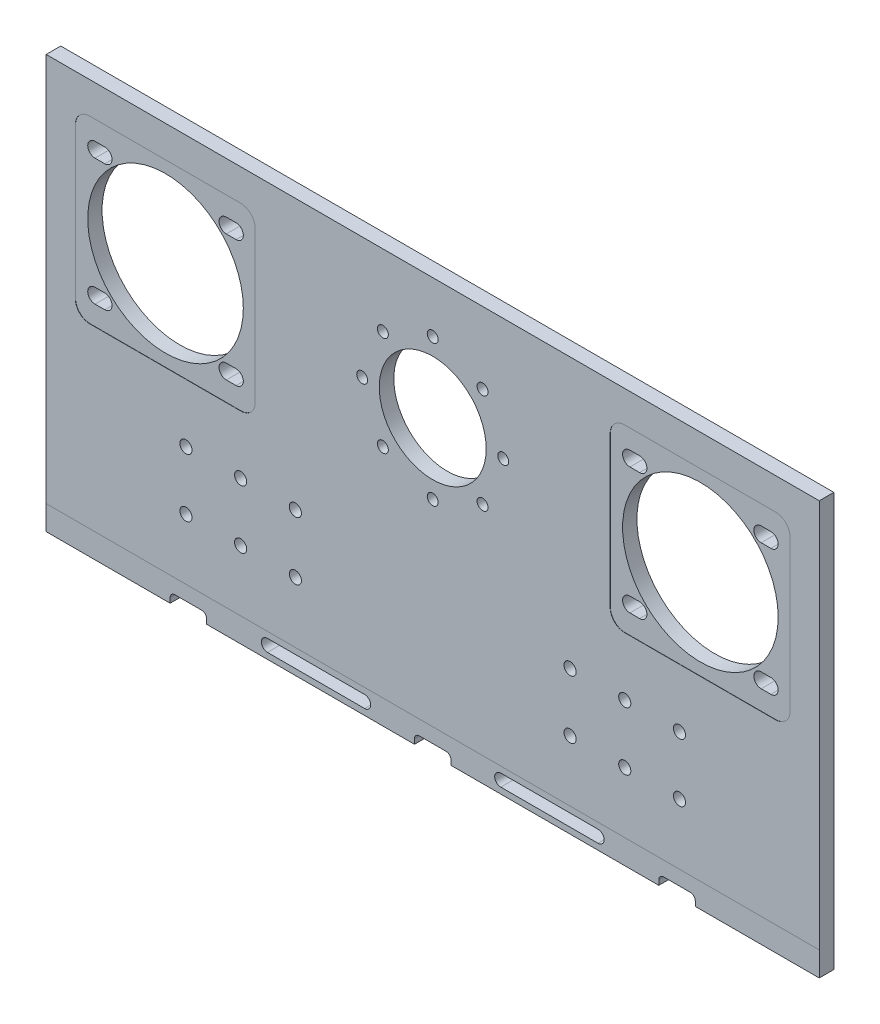
SolidWorks part; units mm, degrees
material "Сталь 45 ГОСТ 1050-88"
ref_plane "Front Plane" through (0, 0, 0) normal (0, 0, 1) x (1, 0, 0)
ref_plane "Top Plane" through (0, 0, 0) normal (0, 1, 0) x (1, 0, 0)
ref_plane "Right Plane" through (0, 0, 0) normal (1, 0, 0) x (0, 0, -1)
sketch "Skizze1" plane through (0, 0, 0) normal (0, 0, 1) x (1, 0, 0)
  line L0 (35, -0.0567) -> (-75, -0.0567)
  line L1 (-75, -0.0567) -> (-185, -0.0567)
  line L2 (35, -50.0567) -> (35, -50.5567)
  line L3 (35, -0.0567) -> (70, -0.0567)
  line L6 (-75, -0.0567) -> (-75, 49.9433)
  line L7 (-75, -0.0567) -> (-75, -110.0567)
  line L8 (0, 25.7745) -> (0, -25.8879)
  line L9 (9.1688, -35.0567) -> (60.8312, -35.0567)
  line L10 (70, -25.8879) -> (70, 25.7745)
  line L11 (60.8312, 34.9433) -> (9.1688, 34.9433)
  line L12 (35, -0.0567) -> (35, -35.0567)
  line L13 (35, -35.0567) -> (70, -35.0567)
  line L14 (70, -0.0567) -> (70, -35.0567)
  line L15 (35, -0.0567) -> (14, -0.0567)
  line L16 (35, -0.0567) -> (35, -50.0567)
  line L19 (35, -0.0567) -> (14, -0.0567)
  line L20 (35, -0.0567) -> (35, 49.9433)
  line L23 (-185, -0.0567) -> (-234, -0.0567)
  line L24 (-185, -0.0567) -> (-185, 49.9433)
  line L25 (-185, 49.9433) -> (-234, 49.9433)
  line L27 (-234, -0.0567) -> (-185, -0.0567)
  line L30 (-185, -0.0567) -> (-185, -50.0567)
  line L31 (-234, 49.9433) -> (84, 49.9433)
  line L33 (-234, -0.0567) -> (14, -0.0567)
  line L35 (14, -0.0567) -> (-234, -0.0567)
  line L39 (-143, -117.5567) -> (-103, -117.5567)
  line L41 (-143, -112.5567) -> (-103, -112.5567)
  line L43 (-7, -117.5567) -> (-47, -117.5567)
  line L44 (-7, -112.5567) -> (-47, -112.5567)
  line L51 (-75, -110.0567) -> (-75, -116.0567)
  line L53 (-67.5, -120.0567) -> (18, -120.0567)
  line L58 (33, -120.0567) -> (84, -120.0567)
  line L59 (-168, -120.0567) -> (-82.5, -120.0567)
  line L66 (33, -118.0567) -> (33, -120.0567)
  line L67 (20, -116.0567) -> (31, -116.0567)
  line L68 (18, -120.0567) -> (18, -118.0567)
  line L70 (-67.5, -118.0567) -> (-67.5, -120.0567)
  line L71 (-80.5, -116.0567) -> (-69.5, -116.0567)
  line L72 (-82.5, -120.0567) -> (-82.5, -118.0567)
  line L74 (-168, -118.0567) -> (-168, -120.0567)
  line L75 (-181, -116.0567) -> (-170, -116.0567)
  line L76 (-183, -120.0567) -> (-183, -118.0567)
  line L77 (-234, -120.0567) -> (-183, -120.0567)
  line L78 (-234, 49.9433) -> (-234, -120.0567)
  line L79 (84, -110.0567) -> (-234, -110.0567)
  line L80 (84, -120.0567) -> (84, 49.9433)
  circle A0 centre (-185, -0.0567) radius 15
  circle A1 centre (35, -0.0567) radius 15
  circle A2 centre (-75, -0.0567) radius 60
  circle A3 centre (-75, -0.0567) radius 22
  arc A4 (-183, -118.0567) -> (-181, -116.0567) centre (-181, -118.0567) cw
  arc A6 (-170, -116.0567) -> (-168, -118.0567) centre (-170, -118.0567) cw
  arc A8 (9.1688, 34.9433) -> (0, 25.7745) centre (35, -0.0567) ccw
  arc A9 (0, -25.8879) -> (9.1688, -35.0567) centre (35, -0.0567) ccw
  arc A10 (60.8312, -35.0567) -> (70, -25.8879) centre (35, -0.0567) ccw
  arc A11 (70, 25.7745) -> (60.8312, 34.9433) centre (35, -0.0567) ccw
  arc A12 (-82.5, -118.0567) -> (-80.5, -116.0567) centre (-80.5, -118.0567) cw
  circle A14 centre (35, -0.1133) radius 27.5
  circle A15 centre (35, -0.0567) radius 32
  circle A16 centre (-185, -0.0567) radius 32
  arc A17 (-67.5, -118.0567) -> (-69.5, -116.0567) centre (-69.5, -118.0567) ccw
  arc A18 (18, -118.0567) -> (20, -116.0567) centre (20, -118.0567) cw
  arc A19 (33, -118.0567) -> (31, -116.0567) centre (31, -118.0567) ccw
  arc A23 (-143, -112.5567) -> (-143, -117.5567) centre (-143, -115.0567) ccw
  arc A24 (-103, -117.5567) -> (-103, -112.5567) centre (-103, -115.0567) ccw
  arc A25 (-7, -117.5567) -> (-7, -112.5567) centre (-7, -115.0567) ccw
  arc A26 (-47, -112.5567) -> (-47, -117.5567) centre (-47, -115.0567) ccw
  point P49 (-169, -118.5631)
  point P63 (-103, -110.0567)
  point P67 (0, -50.5567)
  point P69 (0, -50.0567)
  point P80 (-83, -118.7422)
extrude "Aufsatz-Linear austragen1" add sketch "Skizze1" along normal blind 6
sketch "Skizze2" plane through (0, 0, 0) normal (0, 0, 1) x (1, 0, 0)
  circle A1 centre (-75, -0.0567) radius 12.5
  circle A2 centre (-75, -0.0567) radius 29
  point P1 (-75, 28.9433)
  point P4 (-75, 19.9433)
  point P7 (-54.4939, 20.4494)
  point P8 (-60.8579, 14.0855)
  point P9 (-55, -0.0567)
  point P10 (-60.8579, -14.1988)
  point P11 (-75, -20.0567)
  point P12 (-89.1421, -14.1988)
  point P13 (-95, -0.0567)
  point P14 (-89.1421, 14.0855)
  point P15 (-75, -0.0567)
  point P16 (-46, -0.0567)
  point P17 (-54.4939, -20.5628)
  point P18 (-75, -29.0567)
  point P19 (-95.5061, -20.5628)
  point P20 (-104, -0.0567)
  point P21 (-95.5061, 20.4494)
  point P22 (-75, -0.0567)
sketch "Skizze4" plane through (0, 0, 6) normal (0, 0, 1) x (1, 0, 0)
  line L0 (-214, -23.0567) -> (-210, -23.0567)
  line L2 (-210, 28.9433) -> (-214, 28.9433)
  line L8 (-75, -0.0567) -> (-75, -35.2993) construction
  line L9 (64, 22.9433) -> (60, 22.9433)
  line L11 (-210, -29.0567) -> (-214, -29.0567)
  line L12 (-156, -23.0567) -> (-160, -23.0567)
  line L15 (-160, -29.0567) -> (-156, -29.0567)
  line L16 (-156, 22.9433) -> (-160, 22.9433)
  line L19 (-160, 28.9433) -> (-156, 28.9433)
  line L20 (66, -37.0567) -> (4, -37.0567)
  line L26 (-234, 49.9433) -> (-234, -120.0567)
  line L27 (-234, 49.9433) -> (-234, -100.0567)
  line L28 (-185, 36.9433) -> (-216, 36.9433)
  line L29 (-185, 36.9433) -> (-154, 36.9433)
  line L30 (-148, 30.9433) -> (-148, -31.0567)
  line L31 (-222, 30.9433) -> (-222, -31.0567)
  line L32 (-216, -37.0567) -> (-154, -37.0567)
  line L33 (72, 30.9433) -> (72, -31.0567)
  line L34 (-2, 30.9433) -> (-2, -31.0567)
  line L35 (35, 36.9433) -> (4, 36.9433)
  line L37 (-214, 22.9433) -> (-210, 22.9433)
  line L39 (35, 36.9433) -> (66, 36.9433)
  line L40 (84, 49.9433) -> (84, -100.0567)
  line L41 (10, 28.9433) -> (6, 28.9433)
  line L42 (6, 22.9433) -> (10, 22.9433)
  line L43 (10, -29.0567) -> (6, -29.0567)
  line L44 (6, -23.0567) -> (10, -23.0567)
  line L45 (60, -29.0567) -> (64, -29.0567)
  line L46 (60, 28.9433) -> (64, 28.9433)
  line L47 (64, -23.0567) -> (60, -23.0567)
  circle A19 centre (-185, -0.0567) radius 30
  arc A20 (-148, -31.0567) -> (-154, -37.0567) centre (-154, -31.0567) cw
  arc A21 (-222, -31.0567) -> (-216, -37.0567) centre (-216, -31.0567) ccw
  arc A22 (-216, 36.9433) -> (-222, 30.9433) centre (-216, 30.9433) ccw
  arc A23 (-154, 36.9433) -> (-148, 30.9433) centre (-154, 30.9433) cw
  arc A24 (-210, 22.9433) -> (-210, 28.9433) centre (-210, 25.9433) ccw
  arc A25 (-214, 28.9433) -> (-214, 22.9433) centre (-214, 25.9433) ccw
  arc A26 (-214, -29.0567) -> (-214, -23.0567) centre (-214, -26.0567) cw
  arc A27 (-210, -23.0567) -> (-210, -29.0567) centre (-210, -26.0567) cw
  arc A28 (-156, -29.0567) -> (-156, -23.0567) centre (-156, -26.0567) ccw
  arc A29 (-160, -23.0567) -> (-160, -29.0567) centre (-160, -26.0567) ccw
  arc A30 (-156, 28.9433) -> (-156, 22.9433) centre (-156, 25.9433) cw
  arc A31 (-160, 22.9433) -> (-160, 28.9433) centre (-160, 25.9433) cw
  arc A32 (10, 22.9433) -> (10, 28.9433) centre (10, 25.9433) ccw
  arc A33 (6, 28.9433) -> (6, 22.9433) centre (6, 25.9433) ccw
  arc A34 (10, -23.0567) -> (10, -29.0567) centre (10, -26.0567) cw
  arc A35 (6, -29.0567) -> (6, -23.0567) centre (6, -26.0567) cw
  arc A36 (60, -23.0567) -> (60, -29.0567) centre (60, -26.0567) ccw
  arc A37 (64, -29.0567) -> (64, -23.0567) centre (64, -26.0567) ccw
  arc A38 (64, 28.9433) -> (64, 22.9433) centre (64, 25.9433) cw
  arc A39 (60, 22.9433) -> (60, 28.9433) centre (60, 25.9433) cw
  arc A40 (4, 36.9433) -> (-2, 30.9433) centre (4, 30.9433) ccw
  arc A41 (66, 36.9433) -> (72, 30.9433) centre (66, 30.9433) cw
  arc A42 (72, -31.0567) -> (66, -37.0567) centre (66, -31.0567) cw
  arc A43 (-2, -31.0567) -> (4, -37.0567) centre (4, -31.0567) ccw
  circle A44 centre (35, -0.0567) radius 30
  point P7 (-220, -0.0567)
  point P10 (-185, 34.9433)
  point P87 (35, 34.9433)
  point P88 (70, -0.0567)
extrude "Schnitt-Linear austragen1" cut sketch "Skizze4" against normal blind 0.1
sketch "Skizze8" plane through (0, 0, 6) normal (0, 0, 1) x (1, 0, 0)
  line L0 (84, -120.0567) -> (84, 49.9433) construction
  line L2 (-234, -110.0567) -> (84, -110.0567)
  line L3 (-234, -120.0567) -> (-183, -120.0567)
  line L5 (-234, 49.9433) -> (-234, -120.0567) construction
  line L6 (-234, 49.9433) -> (-234, -120.0567)
  line L7 (84, -120.0567) -> (84, 49.9433)
  arc A2 (-7, -117.5567) -> (-7, -112.5567) centre (-7, -115.0567) ccw
  arc A4 (-47, -112.5567) -> (-47, -117.5567) centre (-47, -115.0567) ccw
  arc A6 (-143, -112.5567) -> (-143, -117.5567) centre (-143, -115.0567) ccw
  arc A8 (-103, -117.5567) -> (-103, -112.5567) centre (-103, -115.0567) ccw
split line "Trennlinie1"
sketch "Эскиз2" plane through (0, 0, 6) normal (0, 0, 1) x (1, 0, 0)
  line L16 (-210, -23.0567) -> (-214, -23.0567)
  line L17 (-214, -29.0567) -> (-210, -29.0567)
  line L18 (-210, 28.9433) -> (-214, 28.9433)
  line L19 (-214, 22.9433) -> (-210, 22.9433)
  line L20 (-160, 22.9433) -> (-156, 22.9433)
  line L21 (-156, 28.9433) -> (-160, 28.9433)
  line L22 (-156, -23.0567) -> (-160, -23.0567)
  line L23 (-160, -29.0567) -> (-156, -29.0567)
  line L24 (60, 22.9433) -> (64, 22.9433)
  line L25 (64, 28.9433) -> (60, 28.9433)
  line L26 (10, 28.9433) -> (6, 28.9433)
  line L27 (6, 22.9433) -> (10, 22.9433)
  line L28 (6, -29.0567) -> (10, -29.0567)
  line L29 (10, -23.0567) -> (6, -23.0567)
  line L30 (60, -29.0567) -> (64, -29.0567)
  line L31 (64, -23.0567) -> (60, -23.0567)
  circle A1 centre (35, -0.0567) radius 32
  circle A2 centre (-185, -0.0567) radius 32 construction
  circle A3 centre (-185, -0.0567) radius 32
  arc A18 (-214, -23.0567) -> (-214, -29.0567) centre (-214, -26.0567) ccw
  arc A19 (-210, -29.0567) -> (-210, -23.0567) centre (-210, -26.0567) ccw
  arc A20 (-214, 28.9433) -> (-214, 22.9433) centre (-214, 25.9433) ccw
  arc A21 (-210, 22.9433) -> (-210, 28.9433) centre (-210, 25.9433) ccw
  arc A22 (-156, 22.9433) -> (-156, 28.9433) centre (-156, 25.9433) ccw
  arc A23 (-160, 28.9433) -> (-160, 22.9433) centre (-160, 25.9433) ccw
  arc A24 (-160, -23.0567) -> (-160, -29.0567) centre (-160, -26.0567) ccw
  arc A25 (-156, -29.0567) -> (-156, -23.0567) centre (-156, -26.0567) ccw
  arc A26 (64, 22.9433) -> (64, 28.9433) centre (64, 25.9433) ccw
  arc A27 (60, 28.9433) -> (60, 22.9433) centre (60, 25.9433) ccw
  arc A28 (6, 28.9433) -> (6, 22.9433) centre (6, 25.9433) ccw
  arc A29 (10, 22.9433) -> (10, 28.9433) centre (10, 25.9433) ccw
  arc A30 (10, -29.0567) -> (10, -23.0567) centre (10, -26.0567) ccw
  arc A31 (6, -23.0567) -> (6, -29.0567) centre (6, -26.0567) ccw
  arc A32 (64, -29.0567) -> (64, -23.0567) centre (64, -26.0567) ccw
  arc A33 (60, -23.0567) -> (60, -29.0567) centre (60, -26.0567) ccw
  circle A34 centre (-185, -0.0567) radius 32
  circle A35 centre (35, -0.0567) radius 32
extrude "Вырез-Вытянуть1" cut sketch "Эскиз2" against normal through all contours L17 A19 L16 A18 | L23 A25 L22 A24 | L21 A23 L20 A22 | L19 A21 L18 A20 | L27 A29 L26 A28 | L25 A27 L24 A26 | L31 A33 L30 A32 | L29 A31 L28 A30
sketch "Skizze9" plane through (0, 0, 0) normal (0, 0, -1) x (-1, 0, 0)
  circle A0 centre (75, -0.0567) radius 15
sketch "Skizze10" plane through (0, 0, 0) normal (0, 0, -1) x (-1, 0, 0)
  line L0 (7, -115.0567) -> (47, -115.0567)
  line L1 (103, -115.0567) -> (143, -115.0567)
  arc A0 (143, -117.5567) -> (143, -112.5567) centre (143, -115.0567) ccw construction
  arc A1 (103, -112.5567) -> (103, -117.5567) centre (103, -115.0567) ccw construction
  arc A2 (47, -117.5567) -> (47, -112.5567) centre (47, -115.0567) ccw construction
  arc A3 (7, -112.5567) -> (7, -117.5567) centre (7, -115.0567) ccw construction
  arc A4 (143, -117.5567) -> (143, -112.5567) centre (143, -115.0567) ccw
  arc A5 (103, -112.5567) -> (103, -117.5567) centre (103, -115.0567) ccw
  arc A6 (47, -117.5567) -> (47, -112.5567) centre (47, -115.0567) ccw
  arc A7 (7, -112.5567) -> (7, -117.5567) centre (7, -115.0567) ccw
  circle A8 centre (7, -115.0567) radius 3.05
  circle A9 centre (47, -115.0567) radius 3.05
  circle A10 centre (143, -115.0567) radius 3.05
  circle A11 centre (103, -115.0567) radius 3.05
  circle A12 centre (27, -115.0567) radius 3.05
  circle A13 centre (123, -115.0567) radius 3.05
  point P19 (123, -115.0567)
  point P20 (27, -115.0567)
split line "Trennlinie2"
sketch "Skizze12" plane through (0, -120.0567, 0) normal (0, -1, 0) x (1, 0, 0)
  line L0 (102.5854, 3) -> (108.6875, 3)
  line L2 (108.6875, 3) -> (108.6875, -1.4999)
  line L3 (108.6875, -1.4999) -> (102.5854, -1.4999)
  line L4 (102.5854, -1.4999) -> (102.5854, 3)
revolve "Rotation1" [suppressed] add sketch "Skizze12" angle 360 about L0
hole_wizard "Durchgangsloch für M41" positions "Skizze17" profile "Skizze18" hole size "M4" standard "DIN" end condition through all
sketch "Skizze17" plane through (0, 0, 0) normal (0, 0, -1) x (-1, 0, 0)
  point P0 (75, 28.9433)
  point P3 (95.5061, 20.4494)
  point P6 (104, -0.0567)
  point P9 (95.5061, -20.5628)
  point P12 (75, -29.0567)
  point P15 (54.4939, -20.5628)
  point P18 (46, -0.0567)
  point P21 (54.4939, 20.4494)
sketch "Skizze18" plane through (-75, 28.9433, 0) normal (1, 0, 0) x (0, 1, 0)
  line L0 (0, 0) -> (0, 6)
  line L1 (0, 6) -> (2.25, 6)
  line L2 (2.25, 6) -> (2.25, 0)
  line L5 (2.25, 0) -> (0, 0)
  line L11 (0, -6.35) -> (0, 107.95) construction
  dimension "Bohrerdurchmesser" = 4.5
  dimension "Bohrungstiefe" = 6
sketch "Skizze19" plane through (0, 0, 6) normal (0, 0, 1) x (1, 0, 0)
  line L0 (84, -120.0567) -> (84, -110.0567) construction
  line L1 (33, -120.0567) -> (84, -120.0567) construction
  line L2 (84, -120.0567) -> (84, -79.6743)
  line L3 (33, -120.0567) -> (84, -120.0567)
  line L4 (26.5, -85.0567) -> (26.5, -61.0567)
  line L5 (26.5, -61.0567) -> (4, -61.0567)
  line L6 (26.5, -120.0567) -> (26.5, -85.0567)
  line L7 (61.5, -85.0567) -> (84, -85.0567)
  line L8 (26.5, -85.0567) -> (4, -85.0567)
  line L9 (4, -61.0567) -> (4, -85.0567)
  line L10 (4, -85.0567) -> (-18.5, -85.0567)
  line L11 (-18.5, -85.0567) -> (-18.5, -61.0567)
  line L12 (-18.5, -61.0567) -> (4, -61.0567)
  line L13 (-131.5, -61.0567) -> (-154, -61.0567)
  line L14 (-234, -110.0567) -> (84, -110.0567) construction
  line L15 (-75, -110.0567) -> (-75, -58.4975) construction
  line L16 (-131.5, -85.0567) -> (-131.5, -61.0567)
  line L17 (-154, -85.0567) -> (-131.5, -85.0567)
  line L18 (-154, -61.0567) -> (-154, -85.0567)
  line L19 (-176.5, -85.0567) -> (-154, -85.0567)
  line L20 (-176.5, -85.0567) -> (-234, -85.0567)
  line L21 (-176.5, -120.0567) -> (-176.5, -85.0567)
  line L22 (-176.5, -61.0567) -> (-154, -61.0567)
  line L23 (-176.5, -85.0567) -> (-176.5, -61.0567)
  line L24 (-183, -120.0567) -> (-234, -120.0567)
  line L25 (-234, -120.0567) -> (-234, -79.6743)
  line L26 (84, -85.0567) -> (26.5, -85.0567)
  point P4 (26.5, -85.0567)
hole_wizard "Ø5.0 (5) Durchmesser Bohrung1" positions "3D-Skizze1" profile "Skizze20" hole size "Ø5.0" standard "DIN" end condition through all
sketch3d "3D-Skizze1"
  point P0 (-176.5, -85.0567, 6)
  point P3 (-176.5, -61.0567, 6)
  point P6 (-154, -61.0567, 6)
  point P9 (-131.5, -61.0567, 6)
  point P12 (-131.5, -85.0567, 6)
  point P15 (-154, -85.0567, 6)
  point P18 (-18.5, -61.0567, 6)
  point P21 (4, -61.0567, 6)
  point P24 (26.5, -61.0567, 6)
  point P27 (26.5, -85.0567, 6)
  point P30 (4, -85.0567, 6)
  point P33 (-18.5, -85.0567, 6)
sketch "Skizze20" plane through (-176.5, -85.0567, 6) normal (1, 0, 0) x (0, -1, 0)
  line L0 (0, 0) -> (0, 6)
  line L1 (0, 6) -> (2.5, 6)
  line L2 (2.5, 6) -> (2.5, 0)
  line L5 (2.5, 0) -> (0, 0)
  line L11 (0, -6.35) -> (0, 107.95) construction
  dimension "Bohrerdurchmesser" = 5
  dimension "Bohrungstiefe" = 6
